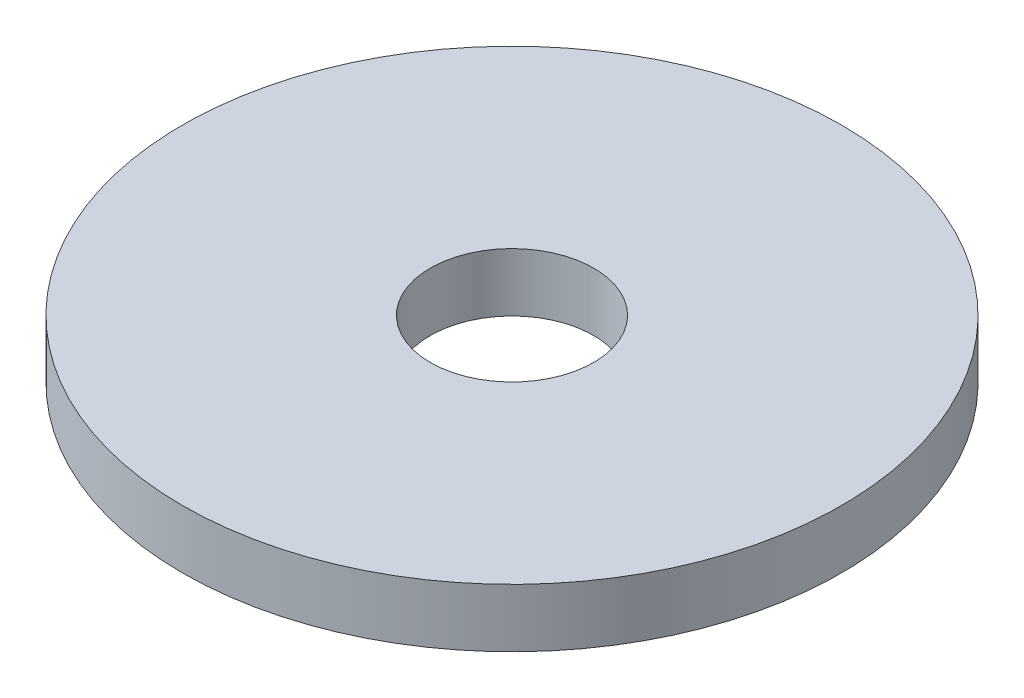
SolidWorks part; units mm, degrees
material "Nylon 101"
ref_plane "Front Plane" through (0, 0, 0) normal (0, 0, 1) x (1, 0, 0)
ref_plane "Top Plane" through (0, 0, 0) normal (0, 1, 0) x (1, 0, 0)
ref_plane "Right Plane" through (0, 0, 0) normal (1, 0, 0) x (0, 0, -1)
sketch "Sketch1" plane through (0, 0, 0) normal (0, 1, 0) x (1, 0, 0)
  circle A0 centre (0, 0) radius 2.921
  dimension "D1" = 5.842
extrude "Boss-Extrude1" add sketch "Sketch1" along normal blind 4 contours A0
sketch "Sketch2" plane through (0, 4, 0) normal (0, 1, 0) x (1, 0, 0)
  circle A0 centre (0, 0) radius 4.2333
  dimension "D1" = 8.4667
extrude "Boss-Extrude2" add sketch "Sketch2" along normal blind 0.75 contours A0
sketch "Sketch3" plane through (0, 4.75, 0) normal (0, 1, 0) x (1, 0, 0)
  circle A0 centre (0, 0) radius 1.05
extrude "Cut-Extrude1" cut sketch "Sketch3" against normal through all
sketch "Sketch4" plane through (0, 0, 0) normal (0, -1, 0) x (1, 0, 0)
  circle A1 centre (0, 0) radius 2.921
  circle A2 centre (0, 0) radius 2.921
  dimension "D1" = 0
extrude "Cut-Extrude2" cut sketch "Sketch4" against normal up to surface (4 mm away) up to face at (0, 4, 2.921)
